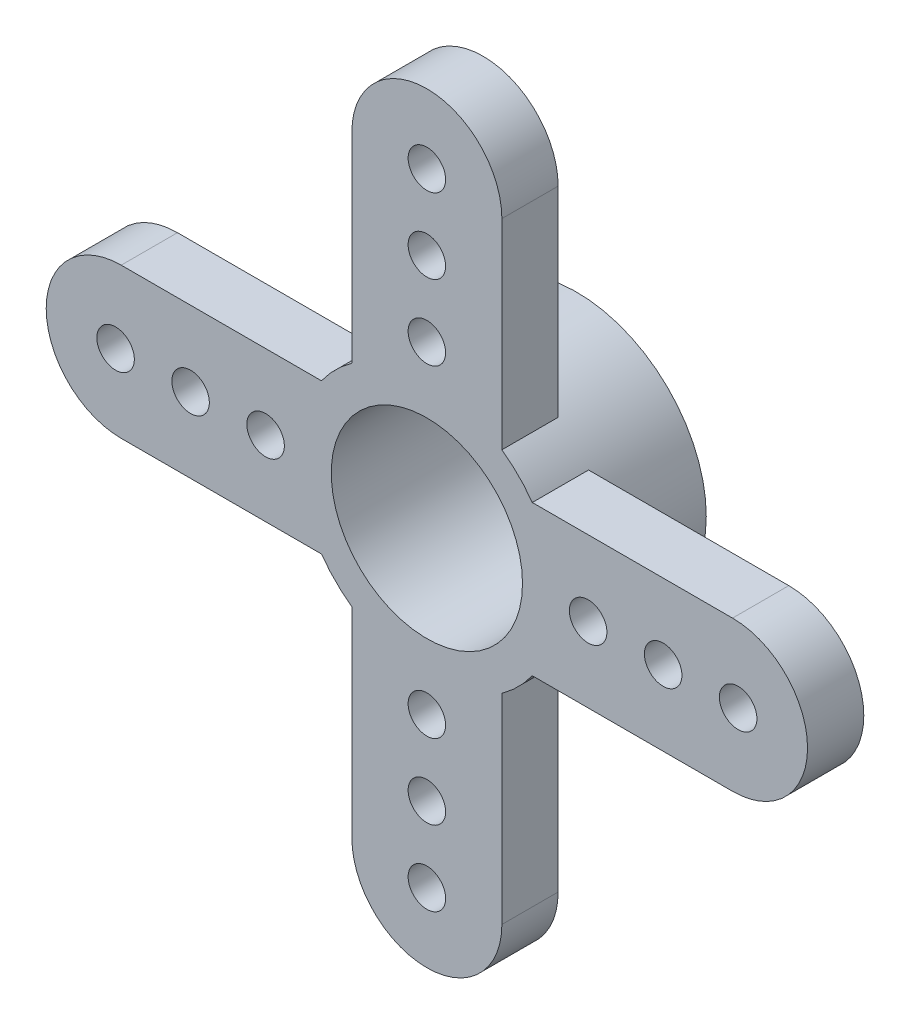
SolidWorks part; units mm, degrees
ref_plane "Front Plane" through (0, 0, 0) normal (0, 0, 1) x (1, 0, 0)
ref_plane "Top Plane" through (0, 0, 0) normal (0, 1, 0) x (1, 0, 0)
ref_plane "Right Plane" through (0, 0, 0) normal (1, 0, 0) x (0, 0, -1)
sketch "Compact_horn_center_OD6p9_profile" plane through (0, 0, 0) normal (0, 0, 1) x (1, 0, 0)
  circle A0 centre (0, 0) radius 3.45
  dimension "D1" = 6.9
extrude "Compact_horn_center_OD6p9" add sketch "Compact_horn_center_OD6p9_profile" along normal blind 1.5
sketch "Horizontal_blades_assumed_width4_profile" plane through (0, 0, 0) normal (0, 0, 1) x (1, 0, 0)
  line L1 (-8.15, -2) -> (8.15, -2)
  line L2 (-8.15, -2) -> (-8.15, 2)
  line L3 (-8.15, 2) -> (8.15, 2)
  line L4 (8.15, -2) -> (8.15, 2)
  dimension "D1" = 16.3
  dimension "D2" = 4
extrude "Horizontal_blades_assumed_width4" add sketch "Horizontal_blades_assumed_width4_profile" along normal blind 1.5
sketch "Vertical_blades_assumed_width4_profile" plane through (0, 0, 0) normal (0, 0, 1) x (1, 0, 0)
  line L1 (-2, -8.15) -> (2, -8.15)
  line L2 (-2, -8.15) -> (-2, 8.15)
  line L3 (-2, 8.15) -> (2, 8.15)
  line L4 (2, -8.15) -> (2, 8.15)
  dimension "D1" = 4
  dimension "D2" = 16.3
extrude "Vertical_blades_assumed_width4" add sketch "Vertical_blades_assumed_width4_profile" along normal blind 1.5
sketch "Rounded_blade_tips" plane through (0, 0, 0) normal (0, 0, 1) x (1, 0, 0)
  circle A0 centre (8.15, 0) radius 2
  circle A1 centre (-8.15, 0) radius 2
  circle A2 centre (0, 8.15) radius 2
  circle A3 centre (0, -8.15) radius 2
  dimension "D1" = 4
  dimension "D2" = 4
  dimension "D3" = 4
  dimension "D4" = 4
extrude "Rounded_tips_span20p3" add sketch "Rounded_blade_tips" along normal blind 1.5
sketch "Hub_projection2p5_total_height4_profile" plane through (0, 0, 0) normal (0, 0, 1) x (1, 0, 0)
  circle A0 centre (0, 0) radius 3.45
  dimension "D1" = 6.9
extrude "Hub_projection2p5_total_height4" add sketch "Hub_projection2p5_total_height4_profile" along normal blind 2.5 from offset 2.5
sketch "Purchased_spline_internals_omitted_profile" plane through (0, 0, 0) normal (0, 0, 1) x (1, 0, 0)
  circle A0 centre (0, 0) radius 2.55
  dimension "D1" = 5.1
extrude "Purchased_spline_internals_omitted" cut sketch "Purchased_spline_internals_omitted_profile" along normal through all from offset 50
sketch "Unmodified_stock_pilot_holes_profile" plane through (0, 0, 0) normal (0, 0, 1) x (1, 0, 0)
  circle A0 centre (-8.3, 0) radius 0.5
  circle A1 centre (-6.3, 0) radius 0.5
  circle A2 centre (-4.3, 0) radius 0.5
  circle A3 centre (4.3, 0) radius 0.5
  circle A4 centre (6.3, 0) radius 0.5
  circle A5 centre (8.3, 0) radius 0.5
  circle A6 centre (0, -8.3) radius 0.5
  circle A7 centre (0, -6.3) radius 0.5
  circle A8 centre (0, -4.3) radius 0.5
  circle A9 centre (0, 4.3) radius 0.5
  circle A10 centre (0, 6.3) radius 0.5
  circle A11 centre (0, 8.3) radius 0.5
  dimension "D1" = 1
  dimension "D2" = 1
  dimension "D3" = 1
  dimension "D4" = 1
  dimension "D5" = 1
  dimension "D6" = 1
  dimension "D7" = 1
  dimension "D8" = 1
  dimension "D9" = 1
  dimension "D10" = 1
  dimension "D11" = 1
  dimension "D12" = 1
extrude "Unmodified_stock_pilot_holes" cut sketch "Unmodified_stock_pilot_holes_profile" along normal through all from offset 50
